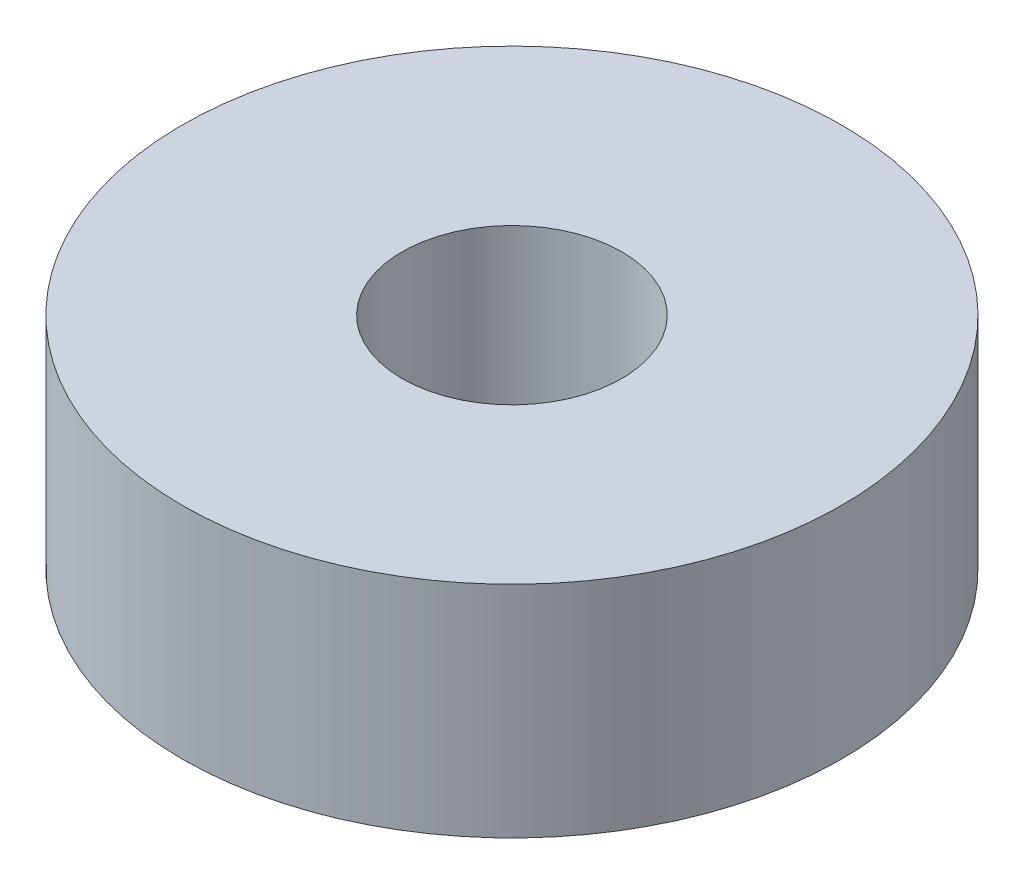
SolidWorks part; units mm, degrees
ref_plane "前视" through (0, 0, 0) normal (0, 0, 1) x (1, 0, 0)
ref_plane "上视" through (0, 0, 0) normal (0, 1, 0) x (1, 0, 0)
ref_plane "右视" through (0, 0, 0) normal (1, 0, 0) x (0, 0, -1)
sketch "草图1" plane through (0, 0, 0) normal (0, 1, 0) x (1, 0, 0)
  circle A0 centre (0, 0) radius 6
  circle A1 centre (0, 0) radius 2
  dimension "D1" = 4
  dimension "D2" = 12
extrude "凸台-拉伸1" add sketch "草图1" along normal blind 4
